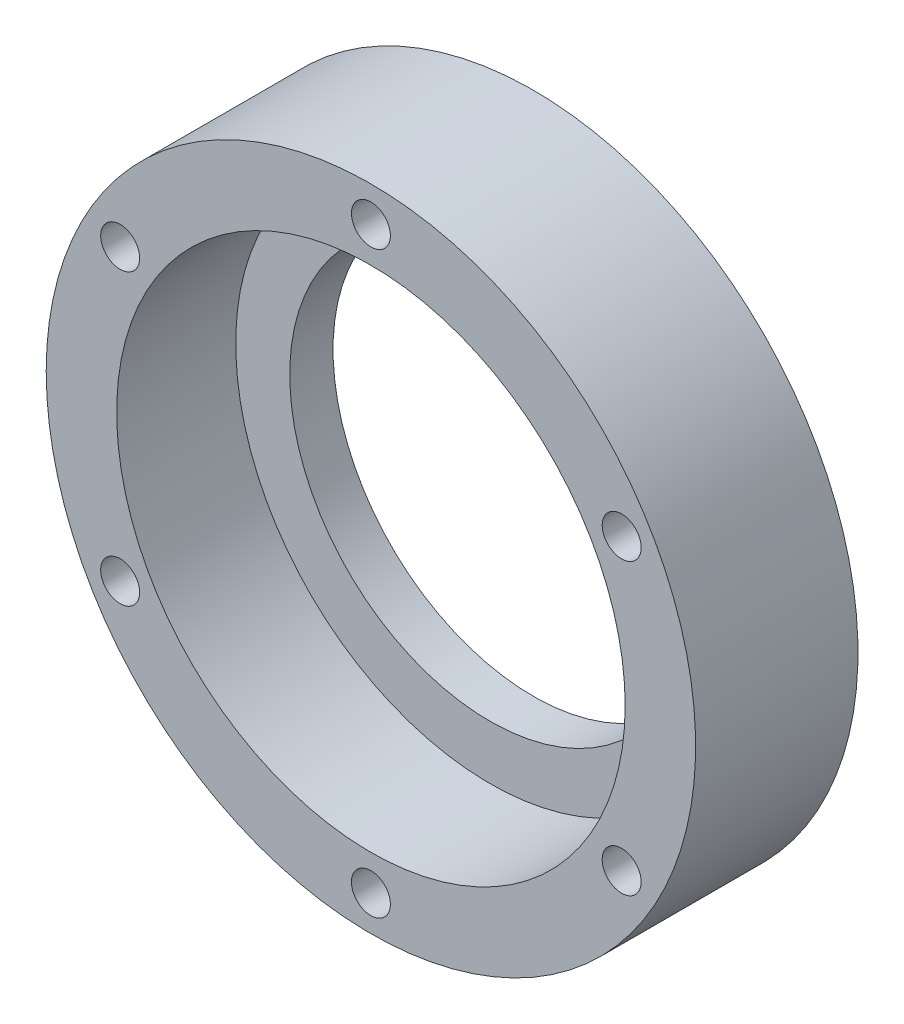
SolidWorks part; units mm, degrees
material "6061 Alloy"
ref_plane "Front" through (0, 0, 0) normal (0, 0, 1) x (1, 0, 0)
ref_plane "Top" through (0, 0, 0) normal (0, 1, 0) x (1, 0, 0)
ref_plane "Right" through (0, 0, 0) normal (1, 0, 0) x (0, 0, -1)
ref_plane "Plane1" through (0, 0, 0) normal (0, -1, 0) x (1, 0, 0)
sketch "Sketch1" plane through (0, 0, 0) normal (0, -1, 0) x (1, 0, 0)
  line L0 (30, 15) -> (0, 15)
  line L1 (0, 15) -> (0, 0)
  line L2 (0, 0) -> (30, 0)
  line L3 (30, 0) -> (30, 15)
  line L4 (0, 15) -> (0, 0) construction
revolve "Revolve1" add sketch "Sketch1" angle 360 about L4
hole_wizard "CSK for M3 Flat Head Machine Screw1" positions "Sketch3" profile "Sketch2" countersink size "M3" standard "ANSI Metric" end condition through all
sketch "Sketch3" plane through (0, 0, 0) normal (0, 0, -1) x (-1, 0, 0)
  point P0 (23.1662, -13.375)
  point P1 (23.1662, 13.375)
  point P2 (0, -26.75)
  point P3 (-23.1662, 13.375)
  point P4 (-23.1662, -13.375)
  point P5 (0, 26.75)
sketch "Sketch2" plane through (-23.1662, -13.375, 0) normal (1, 0, 0) x (0, 1, 0)
  line L0 (0, 0) -> (0, 15)
  line L1 (0, 15) -> (1.8, 15)
  line L2 (1.8, 15) -> (1.8, 1.35)
  line L3 (1.8, 1.35) -> (3.15, 0)
  line L5 (3.15, 0) -> (0, 0)
  line L6 (-1.8, 1.35) -> (-3.15, 0) construction
  line L11 (0, -6.35) -> (0, 107.95) construction
  dimension "Thru Hole Dia." = 3.6
  dimension "Thru Hole Depth" = 15
  dimension "Near C'Sink Dia." = 6.3
  dimension "Near C'Sink Angle" = 90
hole_wizard "Hole1" positions "Sketch5" profile "Sketch4" legacy end condition through all
sketch "Sketch5" plane through (0, 0, 15) normal (0, 0, 1) x (1, 0, 0)
  point P0 (0, 0)
sketch "Sketch4" plane through (0, 0, 15) normal (1, 0, 0) x (0, -1, 0)
  line L0 (0, 0) -> (0, 15)
  line L1 (0, 15) -> (18.5, 15)
  line L2 (18.5, 15) -> (18.5, 11)
  line L3 (18.5, 11) -> (23.4912, 11)
  line L4 (23.4912, 11) -> (23.4912, 0)
  line L5 (23.4912, 0) -> (0, 0)
  line L6 (0, 110) -> (0, -10) construction
  dimension "Diameter" = 37
  dimension "Depth" = 15
  dimension "C-Bore Diameter" = 46.9824
  dimension "C-Bore Depth" = 11
